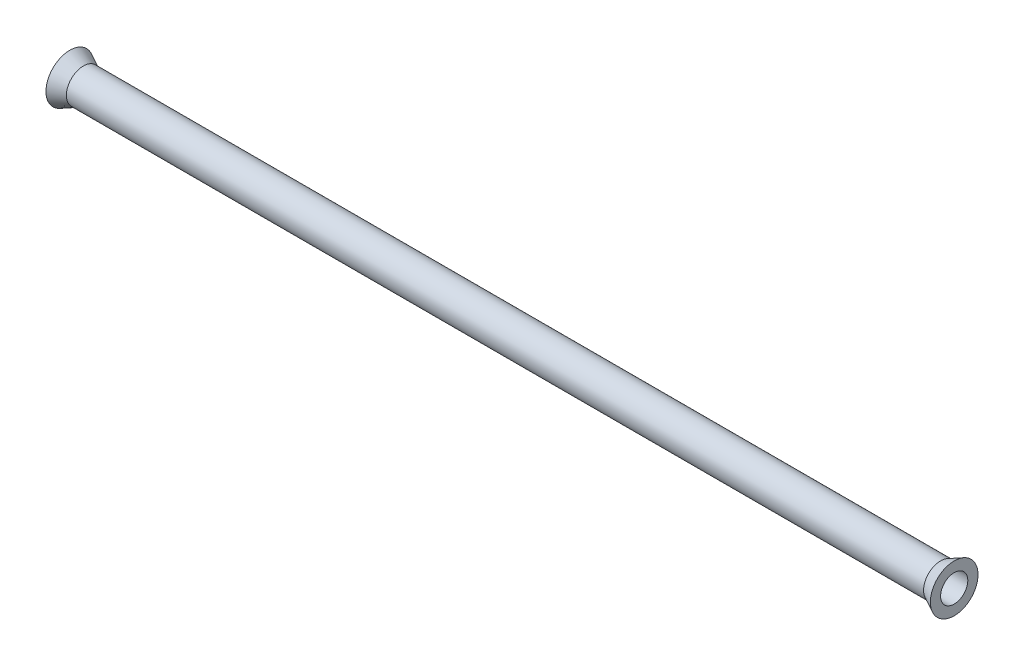
SolidWorks part; units mm, degrees
ref_plane "Спереди" through (0, 0, 0) normal (0, 0, 1) x (1, 0, 0)
ref_plane "Сверху" through (0, 0, 0) normal (0, 1, 0) x (1, 0, 0)
ref_plane "Справа" through (0, 0, 0) normal (1, 0, 0) x (0, 0, -1)
sketch "Эскиз1" plane through (0, 0, 0) normal (0, 0, 1) x (1, 0, 0)
  line L0 (0, 0) -> (-260, 0) construction
  line L1 (-4, 5) -> (-256, 5)
  line L2 (0, 4) -> (-260, 4)
  line L6 (-260, 7) -> (-260, 4)
  line L8 (-260, 7) -> (-256, 5)
  line L9 (0, 7) -> (-4, 5)
  line L10 (0, 7) -> (0, 4)
  point P11 (-130, 5)
  point P13 (-130, 4)
  point P14 (-130, 0)
  dimension "D2" = 5
  dimension "D3" = 4
revolve "Повернуть1" add sketch "Эскиз1" angle 360 about L0
